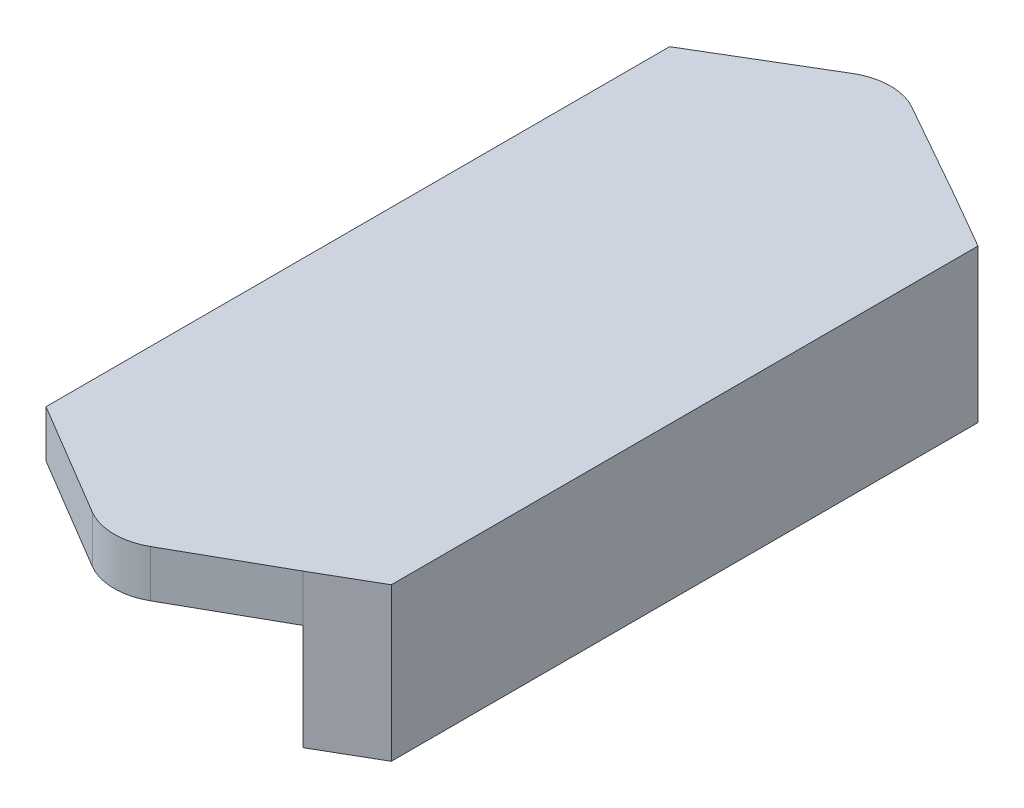
SolidWorks part; units mm, degrees
ref_plane "前视基准面" through (0, 0, 0) normal (0, 0, 1) x (1, 0, 0)
ref_plane "上视基准面" through (0, 0, 0) normal (0, 1, 0) x (1, 0, 0)
ref_plane "右视基准面" through (0, 0, 0) normal (1, 0, 0) x (0, 0, -1)
sketch "草图1" plane through (0, 0, 0) normal (0, 1, 0) x (1, 0, 0)
  line L1 (-30, 31) -> (30, 31)
  line L2 (-30, 31) -> (-30, -31)
  line L3 (-30, -31) -> (30, -31)
  line L4 (30, 31) -> (30, -31)
  line L5 (-30, 31) -> (30, -31) construction
  line L6 (-30, -31) -> (30, 31) construction
  point P0 (0, 0)
  dimension "D1" = 60
  dimension "D2" = 62
extrude "凸台-拉伸1" add sketch "草图1" along normal blind 9
sketch "草图2" plane through (0, 0, 0) normal (0, -1, 0) x (1, 0, 0)
  line L0 (25.2369, 27.6878) -> (23.9062, 25.383) construction
  line L1 (23.9062, 25.383) -> (28.7, 15.9378) construction
  line L4 (25.8, 4) -> (28.7, 15.9378) construction
  line L7 (25.8, 4) -> (28.7, 15.9378)
  line L8 (23.9062, 25.383) -> (28.7, 15.9378)
  line L9 (25.2369, 27.6878) -> (23.9062, 25.383)
  line L10 (25.2369, 27.6878) -> (30, 24.9378)
  line L11 (30, 31) -> (30, -31) construction
  line L12 (30, 24.9378) -> (16.75, 32.5877) construction
  line L13 (30, 24.9378) -> (30, -24.9378)
  line L14 (30, 0) -> (2.2153, 0)
  line L15 (2.2153, 16.95) -> (2.2153, -6.15) construction
  line L16 (2.2153, -7.103) -> (2.2153, 7.103)
  line L17 (2.2153, 7.103) -> (3.7153, 7.103)
  line L18 (3.7153, 7.103) -> (6.2153, 4)
  line L19 (6.2153, 4) -> (25.8, 4)
  line L20 (2.2153, -7.103) -> (3.7153, -7.103)
  line L21 (3.7153, -7.103) -> (6.2153, -4)
  line L22 (25.2369, -27.6878) -> (30, -24.9378)
  line L23 (25.2369, -27.6878) -> (23.9062, -25.383)
  line L24 (23.9062, -25.383) -> (28.7, -15.9378)
  line L25 (25.8, -4) -> (28.7, -15.9378)
  line L26 (6.2153, -4) -> (25.8, -4)
  line M11 (30, -31) -> (30, 31)
  line M12 (30, 31) -> (-30, 31)
  line M13 (-30, 31) -> (-30, -31)
  line M14 (-30, -31) -> (30, -31)
extrude "切除-拉伸1" cut sketch "草图2" against normal blind 20 contours L26 L21 L20 L16 L17 L18 L19 L7 L8 L9 L10 L22 L23 L24 L25 M11 M12 M13 M14
sketch "草图3" plane through (0, 9, 0) normal (0, 1, 0) x (1, 0, 0)
  line L0 (2.2153, 0) -> (30, 0) construction
  line L1 (2.2153, -7.103) -> (2.2153, 7.103) construction
  line L2 (30, -24.9378) -> (30, 24.9378) construction
  line L3 (30, -24.9378) -> (30, 24.9378)
  line L4 (30, 24.9378) -> (25.2369, 27.6878)
  line L5 (25.2369, 27.6878) -> (16.9551, 32.3558)
  line L6 (30, 0) -> (2.2153, 0)
  line L7 (2.2153, -26.5055) -> (2.2153, 26.5055)
  line L8 (12.75, 32.5877) -> (-4.7224, 22.5) construction
  line L9 (2.2153, 26.5055) -> (11.9423, 32.2963)
  line L10 (2.2153, -26.5055) -> (11.9423, -32.2963)
  line L11 (30, -24.9378) -> (25.2369, -27.6878)
  line L12 (25.2369, -27.6878) -> (16.9551, -32.3558)
  circle A0 centre (14.5, 28) radius 5 construction
  circle A1 centre (14.5, 28) radius 5
  circle A2 centre (14.5, -28) radius 5
  line M8 (30, -24.9378) -> (30, 24.9378)
  line M9 (30, 24.9378) -> (25.2369, 27.6878)
  line M10 (25.2369, 27.6878) -> (23.9062, 25.383)
  line M11 (23.9062, 25.383) -> (28.7, 15.9378)
  line M12 (28.7, 15.9378) -> (25.8, 4)
  line M13 (25.8, 4) -> (6.2153, 4)
  line M14 (6.2153, 4) -> (3.7153, 7.103)
  line M15 (3.7153, 7.103) -> (2.2153, 7.103)
  line M16 (2.2153, 7.103) -> (2.2153, -7.103)
  line M17 (2.2153, -7.103) -> (3.7153, -7.103)
  line M18 (3.7153, -7.103) -> (6.2153, -4)
  line M19 (6.2153, -4) -> (25.8, -4)
  line M20 (25.8, -4) -> (28.7, -15.9378)
  line M21 (28.7, -15.9378) -> (23.9062, -25.383)
  line M22 (23.9062, -25.383) -> (25.2369, -27.6878)
  line M23 (25.2369, -27.6878) -> (30, -24.9378)
extrude "凸台-拉伸2" add sketch "草图3" along normal blind 4 contours L6 L3 M9 M10 M11 M12 M13 M14 M15 M16 | A1 L9 L7 L5 M15 M14 M13 M12 M11 M10 | A1 | L6 M8 M16 M17 M18 M19 M20 M21 M22 M23 | L10 A2 L12 L7 M22 M21 M20 M19 M18 M17 | A2
